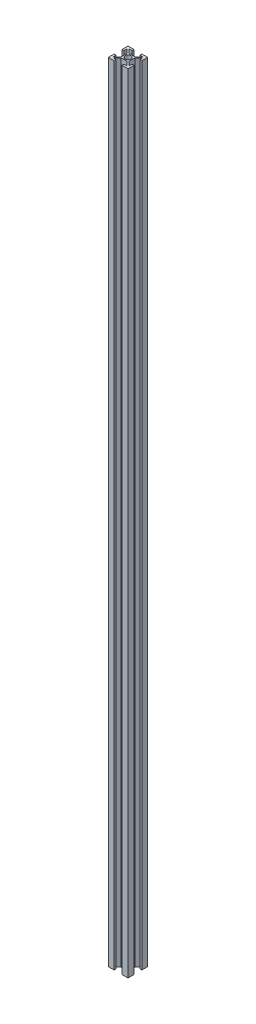
SolidWorks part; units mm, degrees
material "1060 Alloy"
ref_plane "Front Plane" through (0, 0, 0) normal (0, 0, 1) x (1, 0, 0)
ref_plane "Top Plane" through (0, 0, 0) normal (0, 1, 0) x (1, 0, 0)
ref_plane "Right Plane" through (0, 0, 0) normal (1, 0, 0) x (0, 0, -1)
sketch "2020 sketch" plane through (0, 0, 0) normal (0, 1, 0) x (1, 0, 0)
  line L0 (-4, 10) -> (-4, 8)
  line L1 (-10, 10) -> (-4, 10)
  line L2 (-10, 10) -> (-10, 4)
  line L3 (-10, -10) -> (-4, -10)
  line L4 (10, 10) -> (10, 4)
  line L5 (-10, 10) -> (10, -10) construction
  line L6 (-10, -10) -> (10, 10) construction
  line L7 (-4, 8) -> (-7, 8)
  line L8 (-7, 8) -> (-3, 4)
  line L9 (-3, 4) -> (3, 4)
  line L10 (3, 4) -> (7, 8)
  line L11 (7, 8) -> (4, 8)
  line L12 (4, 8) -> (4, 10)
  line L13 (4, 3) -> (4, -3)
  line L14 (8, 7) -> (4, 3)
  line L15 (8, 4) -> (8, 7)
  line L16 (10, 4) -> (8, 4)
  line L17 (8, -4) -> (10, -4)
  line L18 (8, -7) -> (8, -4)
  line L19 (4, -3) -> (8, -7)
  line L20 (3, -4) -> (-3, -4)
  line L21 (7, -8) -> (3, -4)
  line L22 (4, -8) -> (7, -8)
  line L23 (4, -10) -> (4, -8)
  line L24 (-4, -8) -> (-4, -10)
  line L25 (-7, -8) -> (-4, -8)
  line L26 (-3, -4) -> (-7, -8)
  line L27 (-4, -3) -> (-4, 3)
  line L28 (-8, -7) -> (-4, -3)
  line L29 (-8, -4) -> (-8, -7)
  line L30 (-10, -4) -> (-8, -4)
  line L31 (-8, 4) -> (-10, 4)
  line L32 (-8, 7) -> (-8, 4)
  line L33 (-4, 3) -> (-8, 7)
  line L34 (-10, -4) -> (-10, -10)
  line L35 (10, -4) -> (10, -10)
  line L36 (4, 10) -> (10, 10)
  line L37 (4, -10) -> (10, -10)
  circle A0 centre (0, 0) radius 3
  point P0 (0, 0)
  point P14 (4, 9)
  point P42 (0, 0)
  dimension "D9" = 6
  dimension "D1" = 20
  dimension "D2" = 20
  dimension "D3" = 8
  dimension "D4" = 6
  dimension "D5" = 6
  dimension "D6" = 2
  dimension "D7" = 4
  dimension "D8" = 4
extrude "Boss-Extrude1" add sketch "2020 sketch" along normal blind 800 contours A0 | L28 L27 L33 L32 L31 L2 L1 L0 L7 L8 L9 L10 L11 L12 L36 L4 L16 L15 L14 L13 L19 L18 L17 L35 L37 L23 L22 L21 L20 L26 L25 L24 L3 L34 L30 L29
